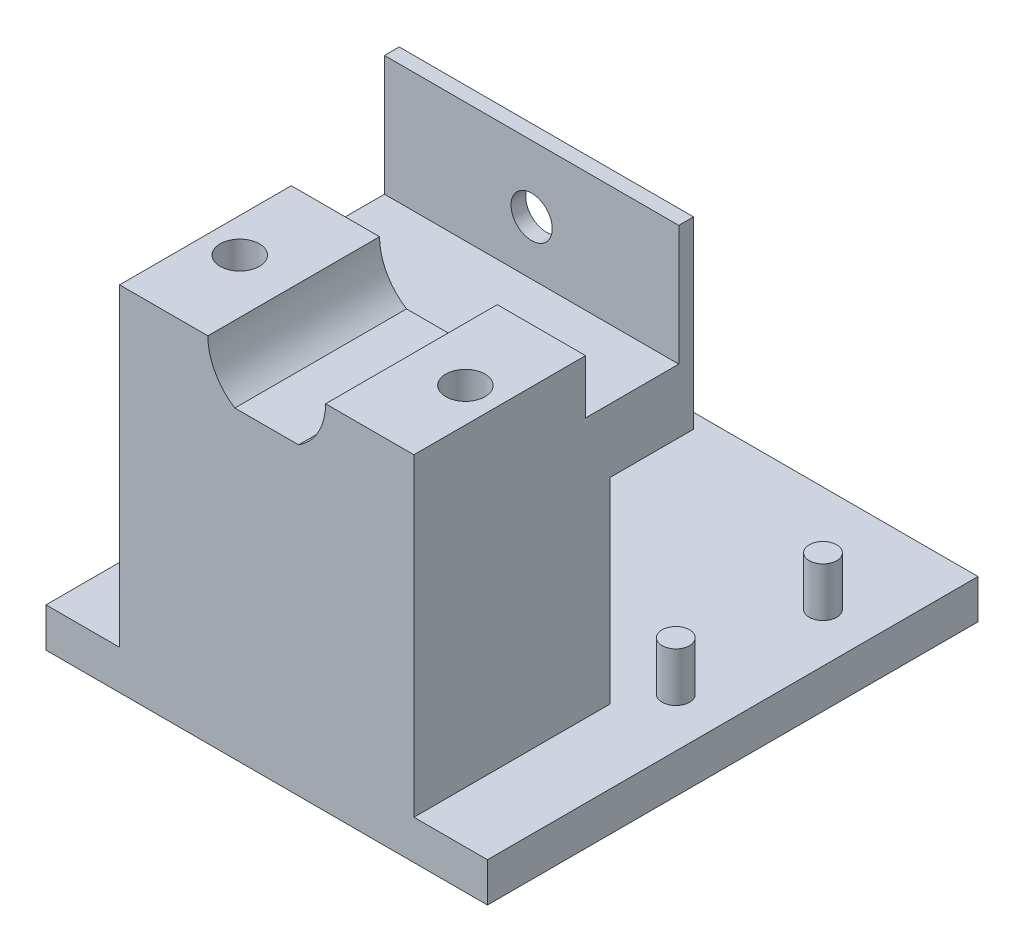
SolidWorks part; units mm, degrees
ref_plane "前基準面" through (0, 0, 0) normal (0, 0, 1) x (1, 0, 0)
ref_plane "上基準面" through (0, 0, 0) normal (0, 1, 0) x (1, 0, 0)
ref_plane "右基準面" through (0, 0, 0) normal (1, 0, 0) x (0, 0, -1)
sketch "草圖2" plane through (0, 0, 0) normal (1, 0, 0) x (0, 0, -1)
  line L1 (0, 4) -> (50, 4)
  line L2 (0, 4) -> (0, 0)
  line L3 (0, 0) -> (50, 0)
  line L4 (50, 4) -> (50, 0)
  dimension "D1" = 4
  dimension "D2" = 50
extrude "填料-伸長2" add sketch "草圖2" along normal mid plane 45
sketch "草圖15" plane through (0, 4, 0) normal (0, 1, 0) x (1, 0, 0)
  line L1 (22.5, 50) -> (22.5, 0) construction
  circle A0 centre (17.5, 39.2) radius 1.4
  circle A1 centre (17.5, 24.2) radius 1.4
  dimension "D1" = 2.8
  dimension "D2" = 15
  dimension "D4" = 5
extrude "填料-伸長8" add sketch "草圖15" along normal blind 5
sketch "草圖3" plane through (0, 4, 0) normal (0, 1, 0) x (1, 0, 0)
  line L1 (-15, 20) -> (15, 20)
  line L2 (-15, 20) -> (-15, 0)
  line L3 (-15, 0) -> (15, 0)
  line L4 (15, 20) -> (15, 0)
  dimension "D1" = 20
  dimension "D2" = 30
extrude "填料-伸長4" add sketch "草圖3" along normal blind 20
sketch "草圖16" plane through (0, 0, 0) normal (0, 0, -1) x (-1, 0, 0)
  line L0 (-15, 24) -> (-15, 36)
  line L1 (-15, 24) -> (15, 24) construction
  line L2 (-15, 36) -> (-6, 36)
  line L3 (-3.25, 31) -> (3.25, 31)
  line L4 (0, -1000) -> (0, 49000) construction
  line L5 (-15, 24) -> (15, 24)
  line L6 (15, 24) -> (15, 36)
  line L7 (15, 36) -> (6, 36)
  line L10 (-3.25, 31) -> (3.25, 31) construction
  arc A0 (-6, 36) -> (-3.25, 31) centre (-0.0795, 36) ccw
  arc A1 (6, 36) -> (3.25, 31) centre (0.0795, 36) cw
  arc A2 (-5.9149, 35) -> (-3.25, 31) centre (-0.0795, 36) ccw construction
  point P13 (0, 24)
  point P17 (0, 31)
  dimension "D2" = 30
  dimension "D3" = 5
extrude "填料-伸長9" add sketch "草圖16" along normal blind 17.5
sketch "草圖18" plane through (0, 0, 0) normal (1, 0, 0) x (0, 0, -1)
  line L0 (17.5, 24) -> (28.5, 24)
  line L1 (28.5, 24) -> (28.5, 42.7488)
  line L2 (28.5, 42.7488) -> (27, 42.7488)
  line L3 (27, 42.7488) -> (27, 30.5)
  line L4 (27, 30.5) -> (17.5, 30.5)
  line L5 (17.5, 36) -> (17.5, 24) construction
  line L6 (17.5, 30.5) -> (17.5, 24)
  line L8 (17.5, 24) -> (20, 24) construction
  dimension "D1" = 1.5
  dimension "D2" = 9.5
  dimension "D3" = 6.5
extrude "填料-伸長10" add sketch "草圖18" along normal mid plane 30
sketch "草圖19" plane through (0, 0, -28.5) normal (0, 0, -1) x (-1, 0, 0)
  circle A0 centre (0, 36) radius 2.1
  dimension "D1" = 4.2
extrude "除料-伸長1" cut sketch "草圖19" against normal up to next
sketch "草圖20" plane through (0, 36, 0) normal (0, 1, 0) x (1, 0, 0)
  circle A0 centre (-11.5, 8.75) radius 2
  circle A1 centre (11.5, 8.75) radius 2
extrude "除料-伸長2" cut sketch "草圖20" against normal blind 10
equation "\"ˋ0\"=50"
